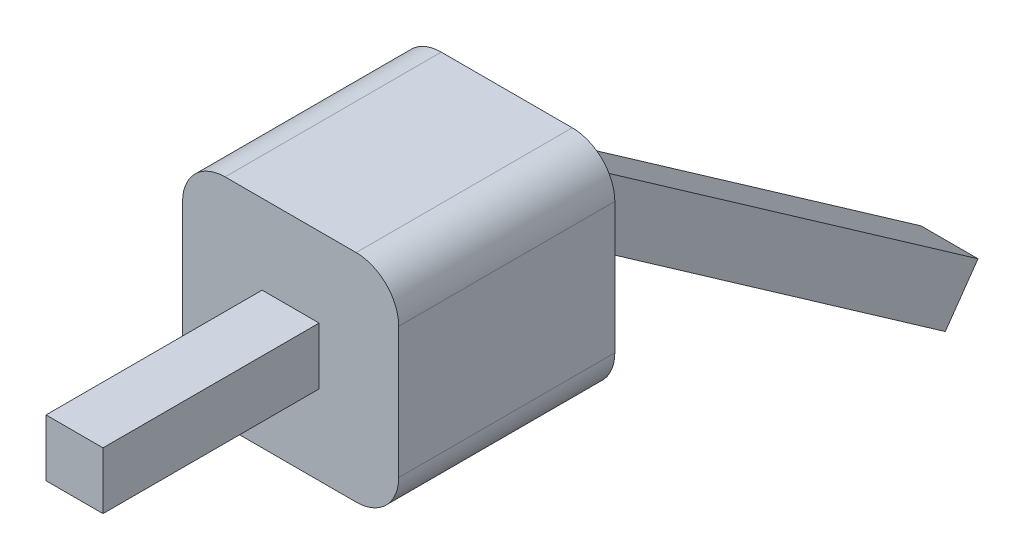
SolidWorks part; units mm, degrees
ref_plane "前视基准面" through (0, 0, 0) normal (0, 0, 1) x (1, 0, 0)
ref_plane "上视基准面" through (0, 0, 0) normal (0, 1, 0) x (1, 0, 0)
ref_plane "右视基准面" through (0, 0, 0) normal (1, 0, 0) x (0, 0, -1)
sketch "草图1" plane through (0, 0, 0) normal (0, 0, 1) x (1, 0, 0)
  line L0 (0, 5.3599) -> (0, -8.0108) construction
  line L1 (-1.27, -0.0191) -> (1.27, -0.0191)
  line L2 (-1.27, -0.0191) -> (-1.27, -2.5591)
  line L3 (-1.27, -2.5591) -> (1.27, -2.5591)
  line L4 (1.27, -0.0191) -> (1.27, -2.5591)
  dimension "D1" = 2.54
  dimension "D2" = 2.54
extrude "拉伸1" add sketch "草图1" along normal blind 2.54
ref_plane "基准面1" through (0, 0, 5.08) normal (0, 0, -1) x (-1, 0, 0)
sketch "草图2" plane through (0, 0, 5.08) normal (0, 0, -1) x (-1, 0, 0)
  line L0 (-1.27, -1.2891) -> (1.27, -1.2891) construction
  line L1 (-1.27, -2.5591) -> (-1.27, -0.0191) construction
  line L2 (1.27, -0.0191) -> (1.27, -2.5591) construction
  line L3 (0, 1.9407) -> (0, -4.2425) construction
  line L5 (-0.335, -0.9541) -> (0.335, -0.9541)
  line L6 (-0.335, -0.9541) -> (-0.335, -1.6241)
  line L7 (-0.335, -1.6241) -> (0.335, -1.6241)
  line L8 (0.335, -0.9541) -> (0.335, -1.6241)
  dimension "D1" = 0.67
  dimension "D2" = 0.67
sketch "草图3" plane through (0, 0, 0) normal (1, 0, 0) x (0, 0, -1)
  line L0 (0.5, -1.2991) -> (-5.08, -1.2991)
  line L1 (-5.08, 1.9407) -> (-5.08, -4.2425) construction
  line L2 (0.5, -1.2991) -> (5.0053, -4.4538)
  line L8 (-2.54, -0.0191) -> (0, -0.0191) construction
  line L9 (0, -2.5591) -> (0, -0.0191) construction
  point P11 (2.54, -1.2991)
  dimension "D5" = 5.5
  dimension "D1" = 5.08
  dimension "D2" = 5.58
  dimension "D3" = 35
  dimension "D4" = 1.28
sweep "扫描1" add profiles "草图2" path "草图3"
fillet "圆角1" radius 0.5 4 edges at (1.27, -0.0191, 1.27) (1.27, -2.5591, 1.27) (-1.27, -2.5591, 1.27) (-1.27, -0.0191, 1.27)
